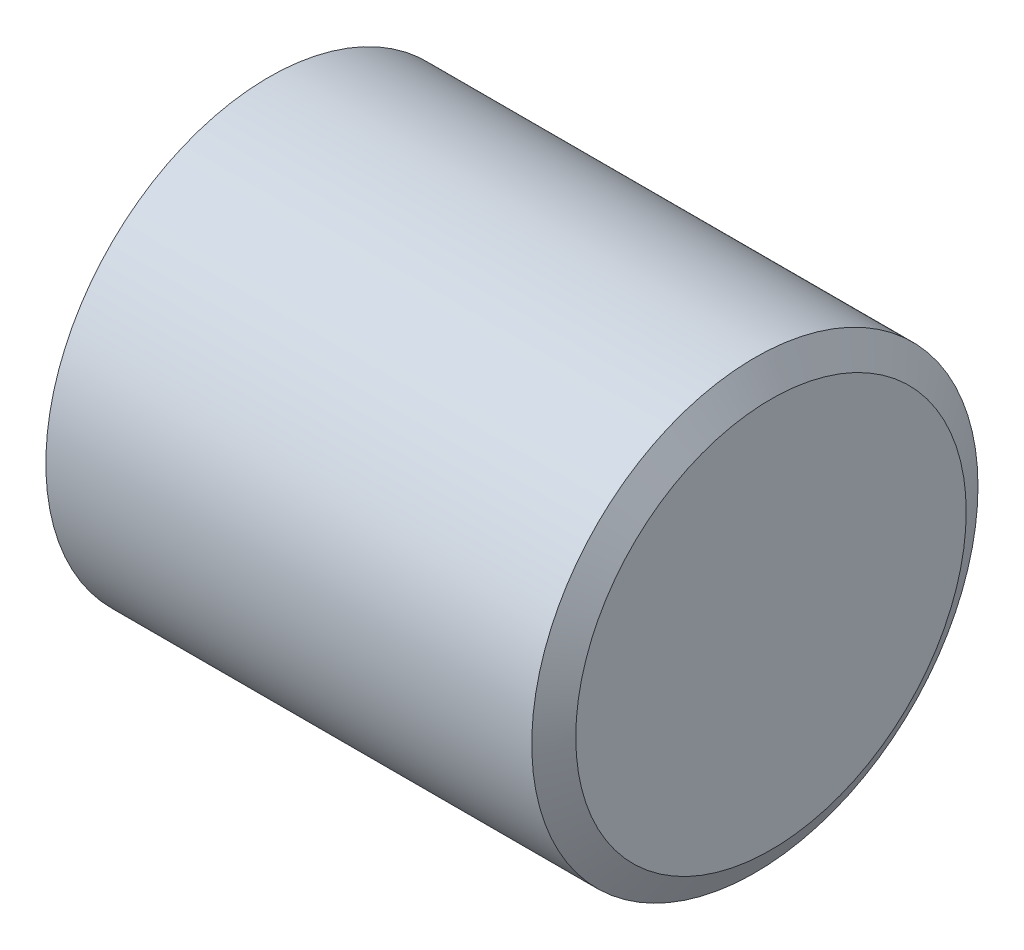
SolidWorks part; units mm, degrees
material "Rubber"
ref_plane "Front Plane" through (0, 0, 0) normal (0, 0, 1) x (1, 0, 0)
ref_plane "Top Plane" through (0, 0, 0) normal (0, 1, 0) x (1, 0, 0)
ref_plane "Right Plane" through (0, 0, 0) normal (1, 0, 0) x (0, 0, -1)
sketch "Sketch1" plane through (0, 0, 0) normal (0, 0, 1) x (1, 0, 0)
  line L1 (0, 0) -> (-10.1723, 0) construction
  line L4 (-3, 2.5) -> (-9, 2.5)
  line L5 (-9, 2.5) -> (-9, 4)
  line L6 (-9, 4) -> (0, 4)
  line L12 (-3, 2.5) -> (-3, 0)
  line L13 (-3, 0) -> (0, 0)
  line L15 (0, 0) -> (0, 4)
  dimension "D1" = 5
  dimension "D2" = 6
  dimension "D3" = 9
  dimension "D4" = 8
revolve "Revolve2" add sketch "Sketch1" angle 360 about L1
chamfer "Chamfer1" distance 0.5 angle 30 1 edges at (0, 0, -4)
